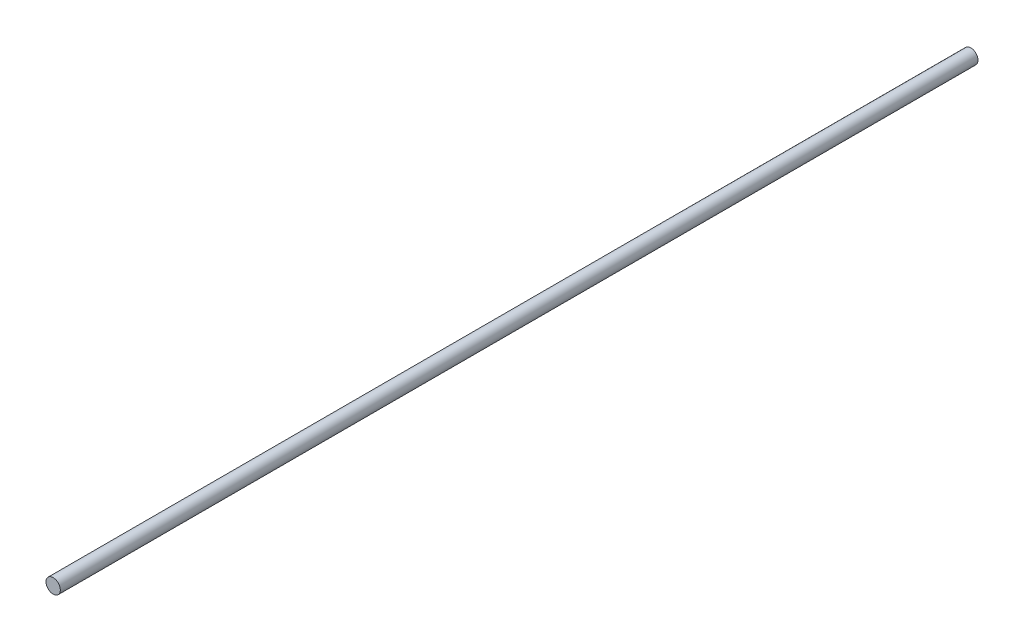
SolidWorks part; units mm, degrees
material "Hexcel AS4C (3000 Filaments)"
ref_plane "Front Plane" through (0, 0, 0) normal (0, 0, 1) x (1, 0, 0)
ref_plane "Top Plane" through (0, 0, 0) normal (0, 1, 0) x (1, 0, 0)
ref_plane "Right Plane" through (0, 0, 0) normal (1, 0, 0) x (0, 0, -1)
sketch "Sketch1" plane through (0, 0, 0) normal (0, 0, 1) x (1, 0, 0)
  circle A0 centre (0, 0) radius 2.5
  dimension "D1" = 5
extrude "Boss-Extrude1" add sketch "Sketch1" along normal blind 320
